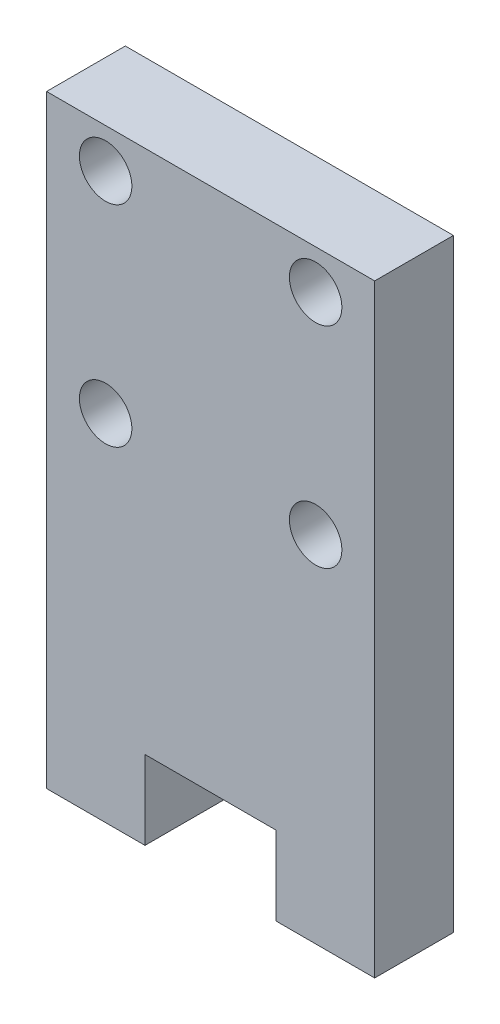
SolidWorks part; units mm, degrees
ref_plane "Plan de face" through (0, 0, 0) normal (0, 0, 1) x (1, 0, 0)
ref_plane "Plan de dessus" through (0, 0, 0) normal (0, 1, 0) x (1, 0, 0)
ref_plane "Plan de droite" through (0, 0, 0) normal (1, 0, 0) x (0, 0, -1)
sketch "Esquisse1" plane through (0, 0, 0) normal (0, 0, 1) x (1, 0, 0)
  line L1 (0, 0) -> (25, 0)
  line L2 (0, 0) -> (0, 40)
  line L3 (0, 40) -> (25, 40)
  line L4 (25, 0) -> (25, 40)
  dimension "D1" = 25
  dimension "D2" = 40
extrude "Boss.-Extru.1" add sketch "Esquisse1" along normal blind 6
sketch "Esquisse2" plane through (0, 0, 6) normal (0, 0, 1) x (1, 0, 0)
  line L0 (25, 40) -> (0, 40) construction
  line L2 (12.5, 40) -> (12.5, 0) construction
  line L3 (0, 0) -> (25, 0) construction
  circle A0 centre (4.5, 37) radius 1.005
  circle A1 centre (20.5, 37) radius 1.005
  circle A2 centre (4.5, 21) radius 1.005
  circle A3 centre (20.5, 21) radius 1.005
  dimension "D1" = 2.01
  dimension "D2" = 2.01
  dimension "D3" = 2.01
  dimension "D4" = 2.01
  dimension "D5" = 8
  dimension "D6" = 8
  dimension "D7" = 16
  dimension "D8" = 3
  dimension "D9" = 8
  dimension "D10" = 16
  dimension "D11" = 3
  dimension "D12" = 8
extrude "Enlèv. mat.-Extru.1" cut sketch "Esquisse2" against normal blind 6
sketch "Esquisse3" plane through (0, 0, 6) normal (0, 0, 1) x (1, 0, 0)
  circle A0 centre (4.5, 37) radius 2
  circle A1 centre (20.5, 37) radius 2
  circle A2 centre (4.5, 21) radius 2
  circle A3 centre (20.5, 21) radius 2
  dimension "D1" = 4
  dimension "D2" = 4
  dimension "D3" = 4
  dimension "D4" = 4
extrude "Enlèv. mat.-Extru.2" cut sketch "Esquisse3" against normal blind 3
sketch "Esquisse4" plane through (0, 0, 0) normal (0, -1, 0) x (1, 0, 0)
  line L0 (0, 6) -> (25, 6) construction
  line L1 (0, 0) -> (7.5, 0)
  line L2 (0, 0) -> (0, 6)
  line L3 (0, 6) -> (7.5, 6)
  line L4 (7.5, 0) -> (7.5, 6)
  line L6 (25, 0) -> (17.5, 0)
  line L7 (25, 0) -> (25, 6)
  line L8 (25, 6) -> (17.5, 6)
  line L9 (17.5, 0) -> (17.5, 6)
  dimension "D1" = 10
  dimension "D2" = 7.5
extrude "Boss.-Extru.2" add sketch "Esquisse4" along normal blind 6
